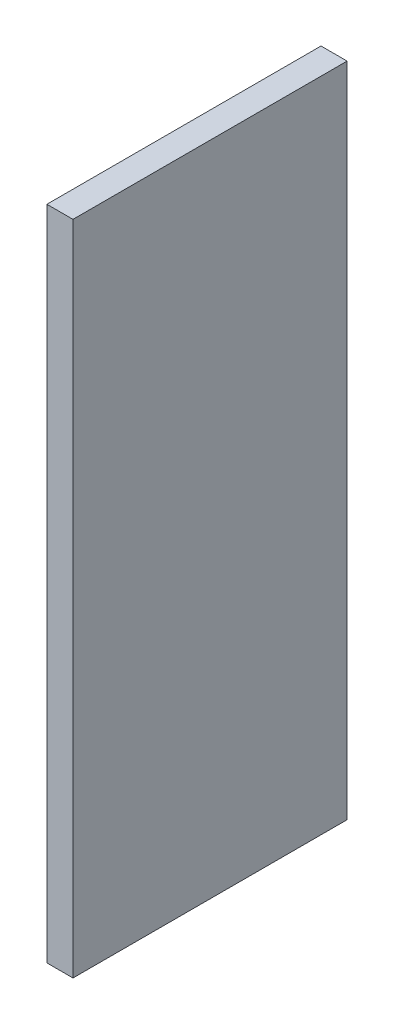
SolidWorks part; units mm, degrees
ref_plane "Спереди" through (0, 0, 0) normal (0, 0, 1) x (1, 0, 0)
ref_plane "Сверху" through (0, 0, 0) normal (0, 1, 0) x (1, 0, 0)
ref_plane "Справа" through (0, 0, 0) normal (1, 0, 0) x (0, 0, -1)
other "Configuration Table"
sketch "Эскиз1" plane through (0, 0, 0) normal (0, 0, 1) x (1, 0, 0)
  line L1 (0, 0) -> (3, 0)
  line L2 (0, 0) -> (0, 74)
  line L3 (0, 74) -> (3, 74)
  line L4 (3, 0) -> (3, 74)
extrude "Бобышка-Вытянуть1" add sketch "Эскиз1" along normal blind 31.5
sketch "Эскиз2" plane through (0, 0, 0) normal (0, 0, 1) x (1, 0, 0)
  line L1 (0, 74) -> (3, 74)
  line L2 (0, 74) -> (0, 75.5)
  line L3 (0, 75.5) -> (3, 75.5)
  line L4 (3, 74) -> (3, 75.5)
extrude "side_rear_extension_1p5mm" add sketch "Эскиз2" along normal blind 31.5
